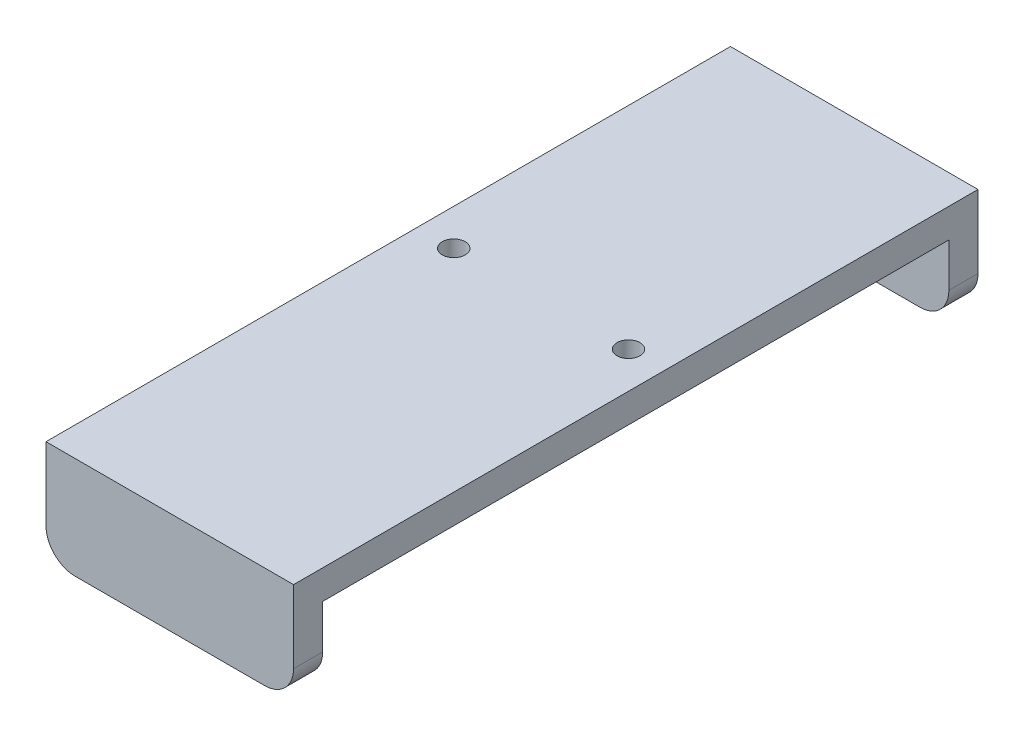
SolidWorks part; units mm, degrees
ref_plane "Front Plane" through (0, 0, 0) normal (0, 0, 1) x (1, 0, 0)
ref_plane "Top Plane" through (0, 0, 0) normal (0, 1, 0) x (1, 0, 0)
ref_plane "Right Plane" through (0, 0, 0) normal (1, 0, 0) x (0, 0, -1)
sketch "Sketch1" plane through (0, 0, 0) normal (1, 0, 0) x (0, 0, -1)
  line L0 (-27.305, 0) -> (27.305, 0)
  line L1 (27.305, 0) -> (27.305, -6.35)
  line L2 (-27.305, 0) -> (-27.305, -6.35)
  point P4 (0, 0)
  dimension "D1" = 54.61
  dimension "D2" = 6.35
extrude "Extrude-Thin1" add sketch "Sketch1" along normal blind 21.59 thin thin type one direction wall 2.54
sketch "Sketch2" plane through (0, 2.54, 0) normal (0, 1, 0) x (1, 0, 0)
  line L0 (0, 0) -> (21.59, 0) construction
  line L1 (21.59, 29.845) -> (21.59, -29.845) construction
  line L2 (10.795, -29.845) -> (10.795, 29.845) construction
  line L4 (21.59, -29.845) -> (0, -29.845) construction
  line L5 (21.59, 29.845) -> (0, 29.845) construction
  line L6 (3.175, 2.54) -> (18.415, 2.54) construction
  circle A2 centre (3.175, 2.54) radius 1
  circle A3 centre (18.415, 2.54) radius 1
  point P14 (10.795, 2.54)
  dimension "D1" = 15.24
  dimension "D2" = 2
  dimension "D3" = 2.54
extrude "Cut-Extrude1" cut sketch "Sketch2" against normal up to next
fillet "Fillet1" radius 2.54 4 edges at (0, -6.35, 28.575) (21.59, -6.35, 28.575) (0, -6.35, -28.575) (21.59, -6.35, -28.575)
